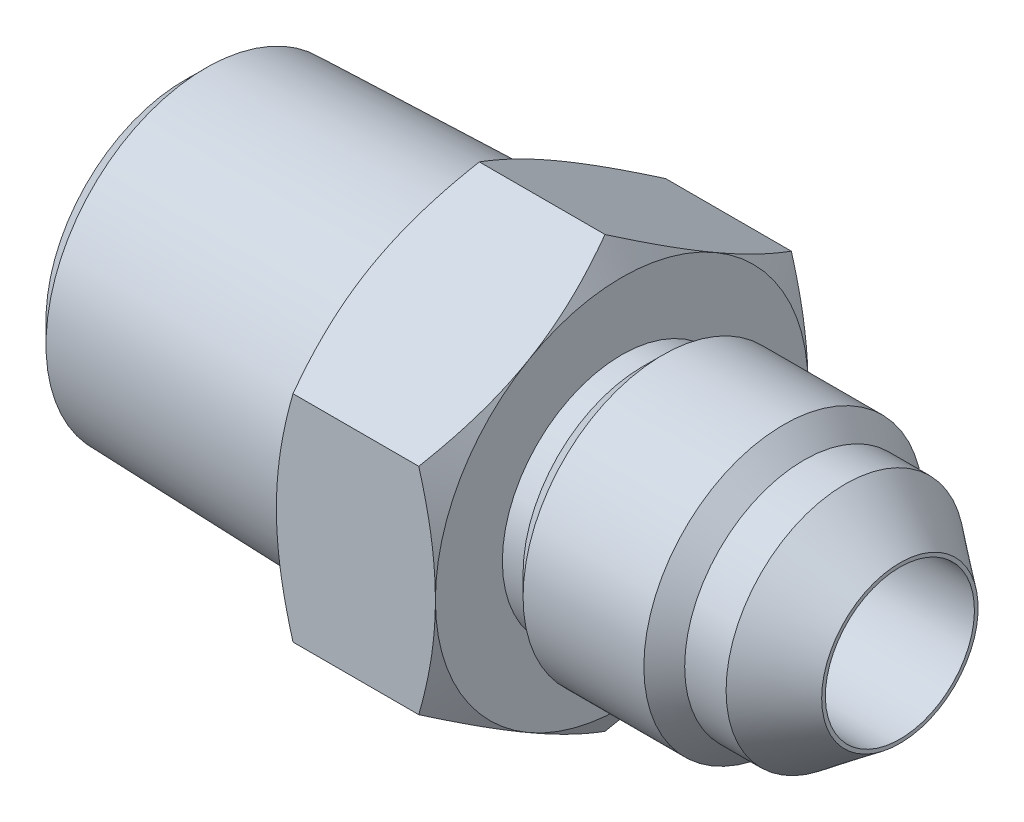
SolidWorks part; units mm, degrees
ref_plane "Front" through (0, 0, 0) normal (0, 0, 1) x (1, 0, 0)
ref_plane "Top" through (0, 0, 0) normal (0, 1, 0) x (1, 0, 0)
ref_plane "Right" through (0, 0, 0) normal (1, 0, 0) x (0, 0, -1)
sketch "Sketch6" plane through (0, 0, 0) normal (0, 0, 1) x (1, 0, 0)
  line L0 (-4.064, 8.5725) -> (-4.064, -8.5725) construction
  line L1 (18.288, 7.1438) -> (18.288, -7.1438) construction
  line L2 (-18.288, 0) -> (18.288, 0)
  line L4 (-18.288, 0) -> (-18.288, 7.1438)
  line L5 (-18.288, 7.1438) -> (18.288, 7.1438)
  line L6 (18.288, 0) -> (18.288, 7.1438)
  line L7 (-18.288, 3.81) -> (-18.288, -3.81) construction
  line L8 (-4.064, 10.287) -> (-4.064, -10.287) construction
  line L9 (4.064, 10.287) -> (4.064, -10.287) construction
  point P4 (4.064, 0)
  point P6 (-4.064, 0)
  dimension "Straight Dia" = 14.2875
  dimension "Length" = 36.576
  dimension "L1" = 14.224
  dimension "Pipe OD" = 17.145
  dimension "L2" = 14.224
  dimension "D1" = 7.62
  dimension "D2" = 20.574
revolve "Revolve3" add sketch "Sketch6" angle 360 about L2
sketch "Sketch14" plane through (18.288, 0, 0) normal (-1, 0, 0) x (0, 0, 1)
  circle A1 centre (0, 0) radius 7.1438
  circle A2 centre (0, 0) radius 7.1438
  dimension "D1" = 0
curve "Helix/Spiral1" pitch 1.4111 height 15.6351 turns 11.08 parameters "Pitch"=1.4111
sketch "Sketch15" plane through (0, 0, 0) normal (0, 0, 1) x (1, 0, 0)
  line L0 (18.288, 7.1438) -> (19.5227, 7.1438)
  line L1 (19.5227, 7.1438) -> (18.9936, 6.2272)
  line L2 (18.9936, 6.2272) -> (18.8172, 6.2272)
  line L3 (18.8172, 6.2272) -> (18.288, 7.1438)
  line L4 (18.9054, 6.2272) -> (18.9054, 7.1438) construction
  line L5 (18.5526, 6.6855) -> (19.2581, 6.6855) construction
  dimension "D1" = 60
  dimension "D2" = 0.1764
  dimension "D3" = 0.7056
ref_plane "Plane1" through (-4.064, 0, 0) normal (1, 0, 0) x (0, 0, -1)
sketch "Sketch12" plane through (-4.064, 0, 0) normal (1, 0, 0) x (0, 0, -1)
  line L1 (0, 10.9985) -> (-9.525, 5.4993)
  line L2 (-9.525, 5.4993) -> (-9.525, -5.4993)
  line L3 (-9.525, -5.4993) -> (0, -10.9985)
  line L4 (0, -10.9985) -> (9.525, -5.4993)
  line L5 (9.525, -5.4993) -> (9.525, 5.4993)
  line L6 (9.525, 5.4993) -> (0, 10.9985)
  circle A0 centre (0, 0) radius 9.525 construction
  dimension "Hex" = 19.05
extrude "Extrude1" add sketch "Sketch12" along normal up to vertex (8.128 mm away) up to point (4.064, 0, 0)
sketch "Sketch7" plane through (0, 0, 0) normal (0, 0, 1) x (1, 0, 0)
  line L0 (-18.288, 0) -> (-18.288, 3.81)
  line L2 (-18.288, 3.81) -> (18.288, 3.81)
  line L4 (18.288, 0) -> (18.288, 7.1438) construction
  line L11 (18.288, 3.81) -> (18.288, 0)
  line L12 (18.288, 0) -> (-18.288, 0)
  line L13 (-18.288, 3.81) -> (-18.288, -3.81) construction
  dimension "ID" = 7.62
sketch "Sketch10" plane through (0, 0, 0) normal (0, 0, 1) x (1, 0, 0)
  line L0 (-18.288, 7.1438) -> (18.288, 7.1438) construction
  line L1 (18.288, 7.1438) -> (19.5227, 7.1438) construction
  line L2 (-4.064, -8.5725) -> (-18.288, -8.1378) construction
  line L3 (4.064, 10.9985) -> (4.064, 5.4993) construction
  line L5 (0, 0) -> (-18.288, 0) construction
  line L6 (6.1659, 7.1438) -> (4.064, 7.1438)
  line L9 (4.064, 6.1002) -> (4.064, 7.1438)
  line L21 (18.288, 7.1438) -> (12.3414, 7.1438)
  line L22 (12.3414, 7.1438) -> (13.3849, 6.1002)
  line L23 (13.3849, 6.1002) -> (15.5016, 6.1002)
  line L24 (15.5016, 6.1002) -> (18.288, 4.0005)
  line L25 (18.288, 4.0005) -> (18.288, 7.1438)
  line L26 (5.1223, 6.1002) -> (4.064, 6.1002)
  line L27 (6.1659, 7.1438) -> (5.1223, 6.1002)
  point P5 (10.5627, -7.1437)
  point P9 (-11.938, -8.3319)
  dimension "D1" = 8.001
  dimension "D2" = 37
  dimension "D3" = 2.1167
  dimension "D5" = 45
  dimension "D4" = 1.0583
  dimension "D6" = 2.8222
  dimension "D7" = 0.127
  dimension "D9" = 6.35
  dimension "D8" = 1.75
revolve "Cut-Revolve6" cut sketch "Sketch10" angle 360 about L2
revolve "Cut-Revolve5" cut sketch "Sketch7" angle 360 about L12
sketch "Sketch13" plane through (0, 0, 0) normal (0, 0, 1) x (1, 0, 0)
  line L0 (-4.064, 10.9985) -> (-4.064, 9.525)
  line L1 (-4.064, 5.4993) -> (-4.064, 10.9985) construction
  line L2 (-4.064, 9.525) -> (-3.2133, 10.9985)
  line L3 (-3.2133, 10.9985) -> (-4.064, 10.9985)
  line L4 (3.2133, 10.9985) -> (4.064, 9.525)
  line L5 (4.064, 10.9985) -> (4.064, 5.4993) construction
  line L6 (4.064, 9.525) -> (4.064, 10.9985)
  line L7 (4.064, 10.9985) -> (3.2133, 10.9985)
  dimension "D2" = 30
revolve "Cut-Revolve7" cut sketch "Sketch13" angle 360 about L2
sketch "Sketch17" plane through (-18.288, 0, 0) normal (-1, 0, 0) x (0, 0, 1)
  circle A0 centre (0, 0) radius 7.1438 construction
  circle A1 centre (0, 0) radius 7.1438
extrude "Cut-Extrude1" cut sketch "Sketch17" against normal up to vertex (14.224 mm away) up to point (-4.064, 0, 0)
ref_plane "Plane2" through (-4.064, 0, 0) normal (1, 0, 0) x (0, 0, -1)
sketch "Sketch19" plane through (-4.064, 0, 0) normal (1, 0, 0) x (0, 0, -1)
  circle A0 centre (0, 0) radius 8.5725
extrude "Boss-Extrude1" add sketch "Sketch19" against normal up to vertex (14.224 mm away) draft 1.75 separate body up to point (-18.288, 0, 0)
sketch "Sketch20" plane through (-18.288, 0, 0) normal (1, 0, 0) x (0, 0, -1)
  circle A1 centre (0, 0) radius 8.1379
  circle A2 centre (0, 0) radius 8.1379 construction
sketch "Sketch21" plane through (0, 0, 0) normal (0, 0, 1) x (1, 0, 0)
  line L0 (-19.4911, 8.0178) -> (-18.3573, 8.0178) construction
  line L1 (-19.6298, 8.258) -> (-18.9242, 7.036) construction
  line L2 (-19.0443, 7.244) -> (-18.8041, 7.244)
  line L3 (-18.9242, 7.036) -> (-18.2187, 8.258) construction
  line L4 (-18.9242, 7.036) -> (-18.8041, 7.244) construction
  line L5 (-18.9242, 8.0178) -> (-18.9242, 8.258) construction
  line L6 (-19.6298, 8.258) -> (-18.2187, 8.258) construction
  line L7 (-18.9242, 8.1379) -> (-18.288, 8.1379) construction
  line L8 (-18.2187, 8.258) -> (-19.5604, 8.1379)
  line L9 (-19.5604, 8.1379) -> (-19.0443, 7.244)
  line L10 (-18.8041, 7.244) -> (-18.2187, 8.258)
  line L11 (-18.9242, 7.036) -> (-18.9242, 7.244) construction
  dimension "D2" = 0.2402
  dimension "D1" = 1.4111
curve "Helix/Spiral2" parameters "Pitch"=1.4111
chamfer "Chamfer1" distance 1.0583 angle 45 1 edges at (-18.288, 0, -8.1379)
sketch "Sketch22" plane through (-4.064, 0, 0) normal (1, 0, 0) x (0, 0, -1)
  circle A1 centre (0, 0) radius 8.5725
  circle A2 centre (0, 0) radius 8.5725
  dimension "D1" = 0
extrude "Boss-Extrude3" add sketch "Sketch22" against normal up to vertex (14.224 mm away) draft 15 up to point (-18.288, 7.1438, 0)
combine bodies "Combine1" operation type add bodies to combine 173 169
sketch "Sketch23" plane through (-18.288, 0, 0) normal (-1, 0, 0) x (0, 0, 1)
  circle A2 centre (0, 0) radius 3.81
extrude "Cut-Extrude2" cut sketch "Sketch23" against normal up to vertex (14.224 mm away) up to point (-4.064, 0, 0)
equation "\"D3@Helix/Spiral1\" = \"L1@Sketch6\"+\"Pitch@Helix/Spiral1\""
equation "\"D2@Sketch15\" = \"Pitch@Helix/Spiral1\"*.125"
equation "\"D3@Sketch15\" = \"Pitch@Helix/Spiral1\"*.5"
equation "\"D3@Sketch10\" = \"Pitch@Helix/Spiral1\"*1.5"
equation "\"D1@Sketch10\" = \"ID@Sketch7\"*1.05"
equation "\"D1@Sketch21\" = \"Pitch@Helix/Spiral2\""
equation "\"D3@Helix/Spiral2\" = \"L2@Sketch6\"+\"Pitch@Helix/Spiral2\""
equation "\"D1@Chamfer1\" = \"Pitch@Helix/Spiral2\"*.75"
equation "\"D4@Sketch10\" = \"Pitch@Helix/Spiral1\"*.75"
equation "\"D6@Sketch10\" = \"Pitch@Helix/Spiral1\"*2"
equation "\"D9@Sketch10\" = \"Pitch@Helix/Spiral2\"*4.5"
equation "\"D2@Sketch6\" = \"Hex@Sketch12\"+.06"
